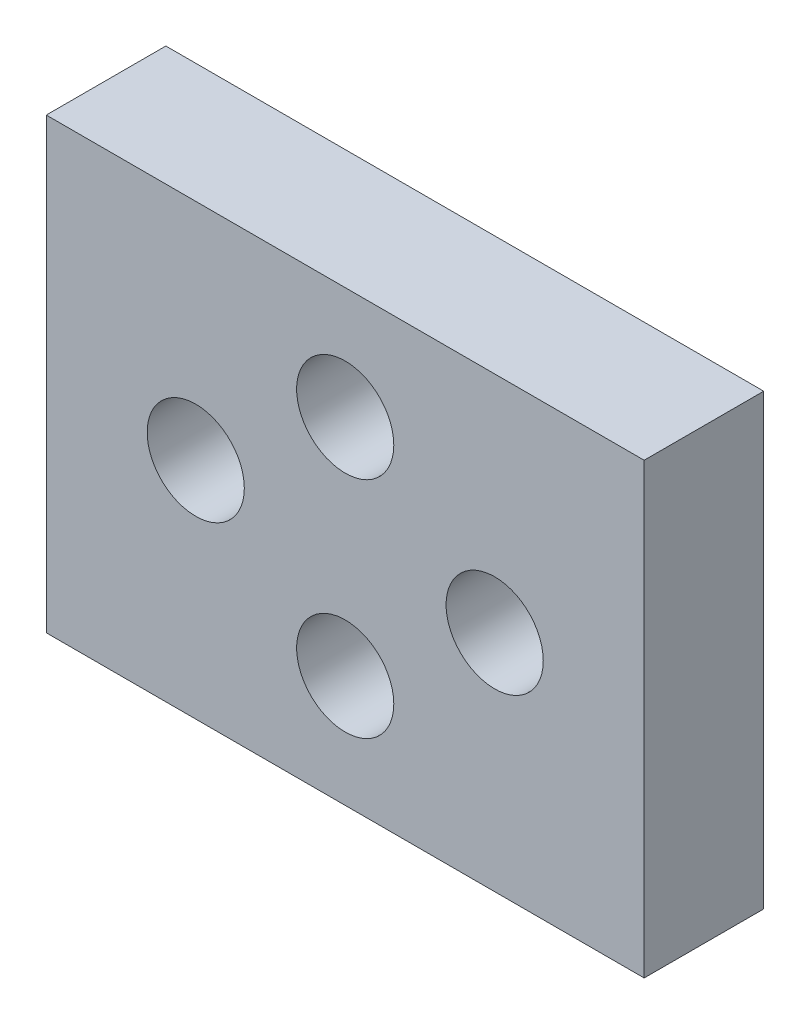
SolidWorks part; units mm, degrees
ref_plane "Front Plane" through (0, 0, 0) normal (0, 0, 1) x (1, 0, 0)
ref_plane "Top Plane" through (0, 0, 0) normal (0, 1, 0) x (1, 0, 0)
ref_plane "Right Plane" through (0, 0, 0) normal (1, 0, 0) x (0, 0, -1)
sketch "Sketch1" plane through (0, 0, 0) normal (0, 0, 1) x (1, 0, 0)
  line L1 (20, -15) -> (-20, -15)
  line L2 (20, -15) -> (20, 15)
  line L3 (20, 15) -> (-20, 15)
  line L4 (-20, -15) -> (-20, 15)
  line L5 (20, -15) -> (-20, 15) construction
  line L6 (20, 15) -> (-20, -15) construction
  point P0 (0, 0)
extrude "Boss-Extrude1" add sketch "Sketch1" along normal blind 8
sketch "Sketch2" plane through (0, 0, 8) normal (0, 0, 1) x (1, 0, 0)
  circle A0 centre (-10, 0) radius 3.25
  circle A1 centre (10, 0) radius 3.25
  circle A2 centre (0, 7.5) radius 3.25
  circle A3 centre (0, -7.5) radius 3.25
  point P8 (0, 0)
  point P12 (0.0456, 3.9132)
  dimension "D3" = 6.5
  dimension "D6" = 6.5
  dimension "D9" = 6.5
  dimension "D12" = 6.5
  dimension "D1" = 10
  dimension "D2" = 15
  dimension "D4" = 30
  dimension "D5" = 15
  dimension "D7" = 20
  dimension "D8" = 7.5
  dimension "D10" = 20
  dimension "D11" = 22.5
extrude "Cut-Extrude1" cut sketch "Sketch2" against normal through all
